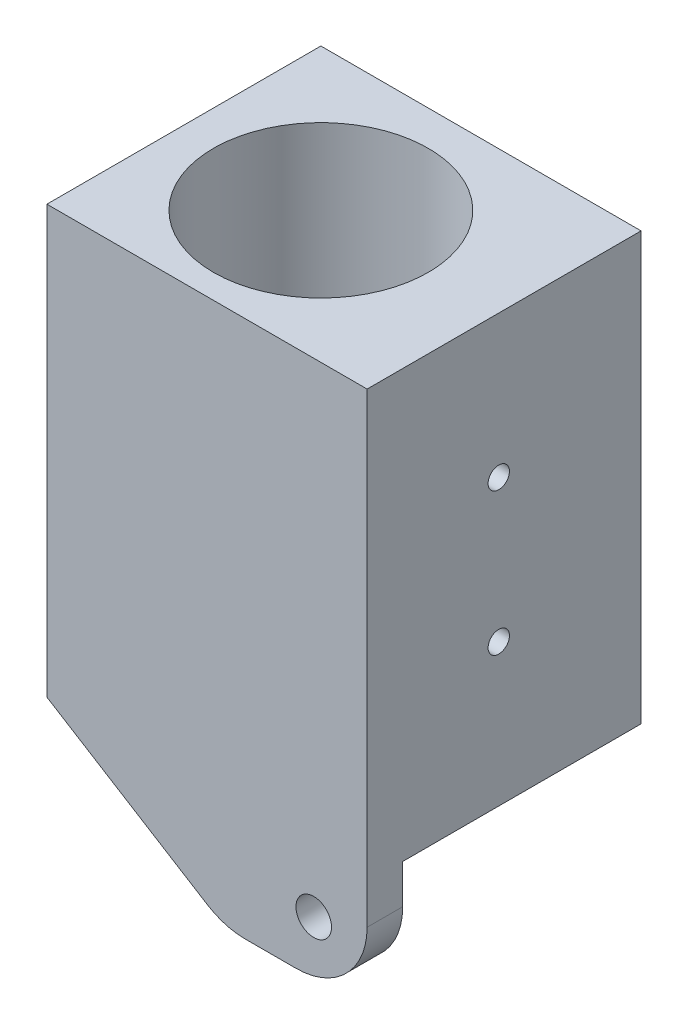
SolidWorks part; units mm, degrees
ref_plane "前基準面" through (0, 0, 0) normal (0, 0, 1) x (1, 0, 0)
ref_plane "上基準面" through (0, 0, 0) normal (0, 1, 0) x (1, 0, 0)
ref_plane "右基準面" through (0, 0, 0) normal (1, 0, 0) x (0, 0, -1)
sketch "草圖1" plane through (0, 0, 0) normal (0, 1, 0) x (1, 0, 0)
  line L1 (-20, 20) -> (25, 20)
  line L2 (-20, 20) -> (-20, -18.5)
  line L3 (-20, -18.5) -> (25, -18.5)
  line L4 (25, 20) -> (25, -18.5)
  dimension "D1" = 20
  dimension "D2" = 38.5
  dimension "D3" = 45
  dimension "D4" = 20
extrude "填料-伸長1" add sketch "草圖1" along normal blind 60
sketch "草圖2" plane through (0, 60, 0) normal (0, 1, 0) x (1, 0, 0)
  circle A0 centre (0, 0) radius 15.1
  dimension "D1" = 30.2
extrude "除料-伸長1" cut sketch "草圖2" against normal blind 50
sketch "草圖3" plane through (0, 0, 18.5) normal (0, 0, 1) x (1, 0, 0)
  line L1 (-20, 0) -> (5, -15.5)
  line L2 (5, -15.5) -> (25, -15.5)
  line L3 (25, -15.5) -> (25, 0)
  line L4 (25, 0) -> (-20, 0)
  circle A1 centre (17.5, -8) radius 2.5
  dimension "D1" = 5
  dimension "D2" = 20
  dimension "D3" = 15.5
  dimension "D4" = 7.5
  dimension "D5" = 8
extrude "填料-伸長2" add sketch "草圖3" against normal blind 5
sketch "草圖4" plane through (25, 0, 0) normal (1, 0, 0) x (0, 0, -1)
  circle A0 centre (0, 20) radius 1.5
  dimension "D1" = 3
  dimension "D2" = 20
extrude "除料-伸長2" cut sketch "草圖4" against normal through all
pattern_linear "直線複製排列1" count 2 spacing 20 along (0, 1, 0) of "除料-伸長2"
fillet "圓角1" radius 10 2 edges at (25, -15.5, 16) (5, -15.5, 16)
